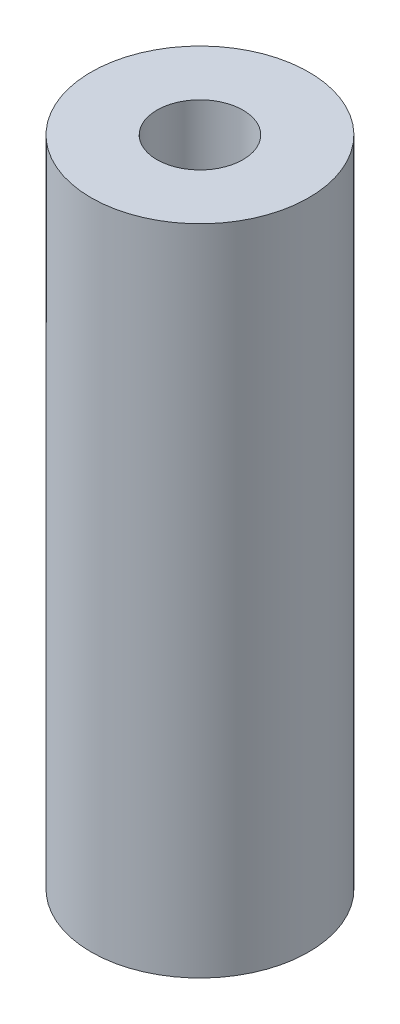
SolidWorks part; units mm, degrees
ref_plane "Front Plane" through (0, 0, 0) normal (0, 0, 1) x (1, 0, 0)
ref_plane "Top Plane" through (0, 0, 0) normal (0, 1, 0) x (1, 0, 0)
ref_plane "Right Plane" through (0, 0, 0) normal (1, 0, 0) x (0, 0, -1)
sketch "Sketch1" plane through (0, 0, 0) normal (0, 1, 0) x (1, 0, 0)
  circle A0 centre (0, 0) radius 0.79
  circle A1 centre (0, 0) radius 2
  dimension "D1" = 1.58
  dimension "D2" = 4
extrude "Boss-Extrude1" add sketch "Sketch1" along normal blind 12
